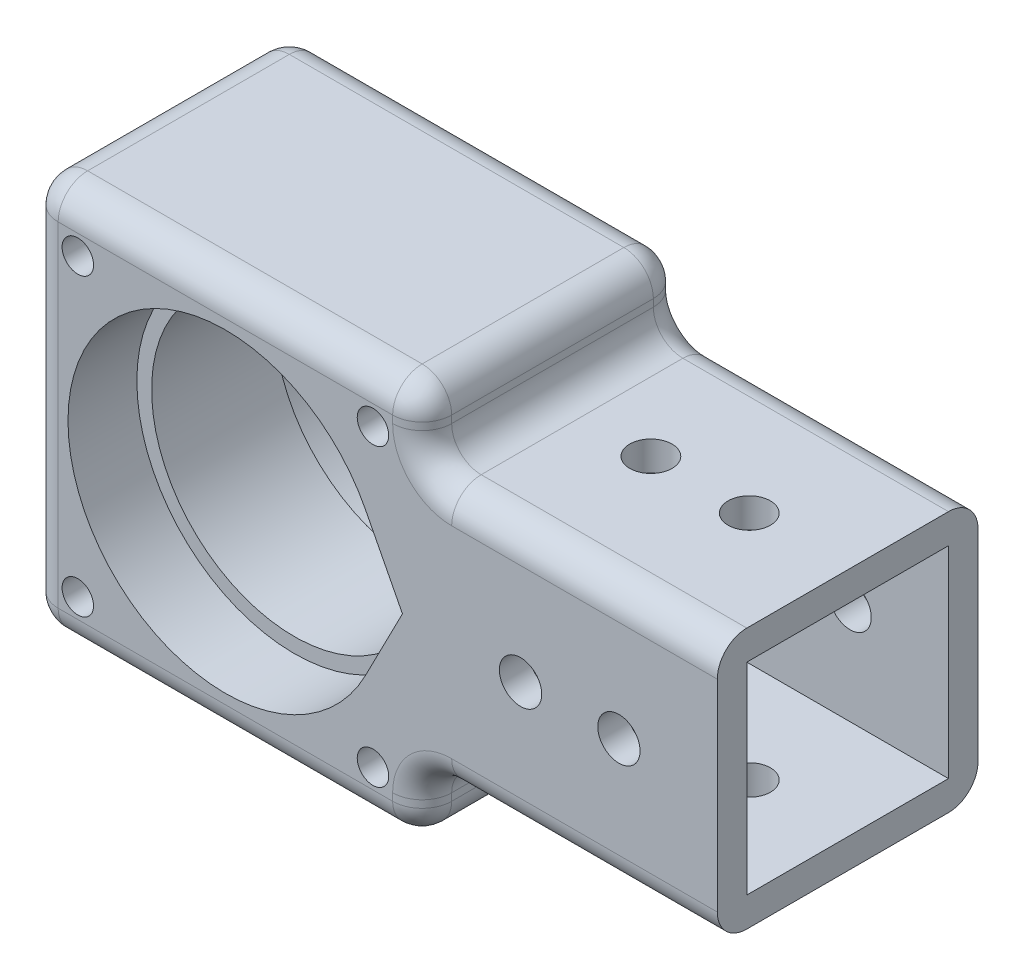
SolidWorks part; units mm, degrees
ref_plane "前视基准面" through (0, 0, 0) normal (0, 0, 1) x (1, 0, 0)
ref_plane "上视基准面" through (0, 0, 0) normal (0, 1, 0) x (1, 0, 0)
ref_plane "右视基准面" through (0, 0, 0) normal (1, 0, 0) x (0, 0, -1)
other "Configuration Table"
sketch "草图1" plane through (0, 0, 0) normal (1, 0, 0) x (0, 0, -1)
  line L1 (-8.75, -8.75) -> (8.75, -8.75)
  line L2 (-8.75, -8.75) -> (-8.75, 8.75)
  line L3 (-8.75, 8.75) -> (8.75, 8.75)
  line L4 (8.75, -8.75) -> (8.75, 8.75)
  line L5 (-8.75, -8.75) -> (8.75, 8.75) construction
  line L6 (-8.75, 8.75) -> (8.75, -8.75) construction
  point P0 (0, 0)
  dimension "D1" = 17.5
  dimension "D2" = 17.5
extrude "凸台-拉伸1" add sketch "草图1" along normal blind 30
sketch "草图2" plane through (0, 0, 0) normal (-1, 0, 0) x (0, 0, 1)
  line L1 (-8.75, -8.75) -> (8.75, -8.75)
  line L2 (-8.75, -8.75) -> (-8.75, 8.75)
  line L3 (-8.75, 8.75) -> (8.75, 8.75)
  line L4 (8.75, -8.75) -> (8.75, 8.75)
  line L5 (-8.75, -8.75) -> (8.75, 8.75) construction
  line L6 (-8.75, 8.75) -> (8.75, -8.75) construction
  line L7 (-10.25, -10.25) -> (10.25, -10.25)
  line L8 (-10.25, -10.25) -> (-10.25, 10.25)
  line L9 (-10.25, 10.25) -> (10.25, 10.25)
  line L10 (10.25, -10.25) -> (10.25, 10.25)
  line L11 (-10.25, -10.25) -> (10.25, 10.25) construction
  line L12 (-10.25, 10.25) -> (10.25, -10.25) construction
  point P0 (0, 0)
  point P7 (0, 0)
  dimension "D1" = 20.5
  dimension "D2" = 20.5
extrude "凸台-拉伸2" add sketch "草图2" against normal blind 2
sketch "草图3" plane through (0, 0, 0) normal (-1, 0, 0) x (0, 0, 1)
  line L5 (-10.25, -10.25) -> (10.25, -10.25)
  line L6 (-10.25, -10.25) -> (-10.25, 10.25)
  line L7 (-10.25, 10.25) -> (10.25, 10.25)
  line L8 (13.25, -13.25) -> (13.25, 13.25)
  line L9 (13.25, 13.25) -> (-13.25, 13.25)
  line L10 (-13.25, 13.25) -> (-13.25, -13.25)
  line L11 (-13.25, -13.25) -> (13.25, -13.25)
  line L12 (13.25, -13.25) -> (13.25, 13.25)
  line L13 (13.25, 13.25) -> (-13.25, 13.25)
  line L14 (-13.25, 13.25) -> (-13.25, -13.25)
  line L15 (-13.25, -13.25) -> (13.25, -13.25)
  line L16 (10.25, -10.25) -> (10.25, 10.25)
  line L17 (-10.25, -10.25) -> (10.25, 10.25) construction
  line L18 (-10.25, 10.25) -> (10.25, -10.25) construction
  point P0 (0, 0)
  dimension "D1" = 3
extrude "凸台-拉伸3" add sketch "草图3" against normal blind 30
sketch "草图4" plane through (0, 13.25, 0) normal (0, 1, 0) x (1, 0, 0)
  line L0 (-1000, 0) -> (49000, 0) construction
  line L1 (0, -13.25) -> (0, 13.25) construction
  circle A0 centre (10, 0) radius 2.15
  circle A1 centre (20, 0) radius 2.15
  dimension "D1" = 4.3
  dimension "D2" = 4.3
  dimension "D4" = 10
  dimension "D5" = 10
sketch "草图5" plane through (0, 0, -13.25) normal (0, 0, -1) x (-1, 0, 0)
  line L1 (-1030, 0) -> (48970, 0) construction
  line L2 (-30, 13.25) -> (-30, -13.25) construction
  line L3 (0, 13.25) -> (0, -13.25) construction
  circle A0 centre (-20, 0) radius 2.15
  circle A1 centre (-10, 0) radius 2.15
  point P7 (-30, 0)
  dimension "D3" = 4.3
  dimension "D4" = 4.3
  dimension "D1" = 10
  dimension "D2" = 10
sketch "草图6" plane through (0, 0, 0) normal (-1, 0, 0) x (0, 0, 1)
  line L0 (-13.25, 2.15) -> (-13.25, -2.15) construction
  line L5 (-23.25, -20) -> (-3.25, -20)
  line L6 (-23.25, -20) -> (-23.25, 20)
  line L7 (-23.25, 20) -> (-3.25, 20)
  line L8 (-3.25, -20) -> (-3.25, 20)
  line L9 (-23.25, -20) -> (-3.25, 20) construction
  line L10 (-23.25, 20) -> (-3.25, -20) construction
  line L11 (-13.25, 20) -> (-13.25, -20)
  point P0 (0, 0)
  point P1 (-13.25, 0)
  line M3 (-13.25, -13.25) -> (13.25, -13.25)
  line M5 (13.25, 13.25) -> (-13.25, 13.25)
  line M6 (-13.25, 13.25) -> (-13.25, -13.25)
  dimension "D1" = 20
  dimension "D2" = 40
extrude "切除-拉伸6" cut sketch "草图4" against normal through all
extrude "凸台-拉伸5" add sketch "草图6" along normal blind 40 contours L8 M3 M5 M6 | L7 L11 L8 M5 | L11 L5 L8 M3
sketch "草图14" plane through (0, 0, -13.25) normal (0, 0, -1) x (-1, 0, 0)
  line L0 (20, -1020) -> (20, 48980) construction
  line L1 (0, 20) -> (40, 20)
  line L2 (0, 20) -> (0, -20)
  line L3 (0, -20) -> (40, -20)
  line L4 (40, 20) -> (40, -20)
  line L5 (-201030, 0) -> (248970, 0) construction
  line L7 (0, 20) -> (5, 20)
  line L8 (0, 20) -> (0, 15)
  line L9 (0, 15) -> (5, 15)
  line L10 (5, 20) -> (5, 15)
  circle A0 centre (20, 0) radius 15
  circle A1 centre (5, 15) radius 1.6
  circle A2 centre (35, 15) radius 1.6
  circle A3 centre (35, -15) radius 1.6
  circle A4 centre (5, -15) radius 1.6
  point P9 (20, -20)
  dimension "D1" = 30
  dimension "D4" = 3.2
  dimension "D2" = 5
  dimension "D3" = 5
  dimension "D5" = 4
extrude "切除-拉伸9" cut sketch "草图14" against normal through all contours A0 L0 | L0 A0 | A4 | A3 | A2 | A1
extrude "切除-拉伸10" cut sketch "草图5" against normal through all
sketch "草图15" plane through (30, 0, 0) normal (1, 0, 0) x (0, 0, -1)
  line L1 (-8.75, -8.75) -> (8.75, -8.75)
  line L2 (-8.75, -8.75) -> (-8.75, 8.75)
  line L3 (-8.75, 8.75) -> (8.75, 8.75)
  line L4 (8.75, -8.75) -> (8.75, 8.75)
  line L5 (-8.75, -8.75) -> (8.75, 8.75) construction
  line L6 (-8.75, 8.75) -> (8.75, -8.75) construction
  point P0 (0, 0)
extrude "切除-拉伸12" cut sketch "草图15" against normal blind 28
sketch "草图16" plane through (0, 0, -3.25) normal (0, 0, 1) x (1, 0, 0)
  line L0 (-20, 0) -> (-3, 0)
  line L1 (-3, 0) -> (-6.7961, 7.1174)
  line L2 (-3, 0) -> (-6.7647, -7.0587)
  line L3 (-6.7647, -7.0587) -> (-6.7961, 7.1174)
  circle A0 centre (-20, 0) radius 15 construction
  circle M19 centre (-20, 0) radius 15
  dimension "D1" = 17
extrude "切除-拉伸13" cut sketch "草图16" against normal blind 28 contours L0 L1 M19 | L2 L0 M19
sketch "草图17" plane through (0, 20, 0) normal (0, 1, 0) x (1, 0, 0)
  line L0 (-20, 13.25) -> (-20, 3.25)
  line L1 (-40, 13.25) -> (0, 13.25) construction
  line L2 (-40, 3.25) -> (0, 3.25) construction
  circle A0 centre (-20, 8.25) radius 1.5
  dimension "D1" = 3
extrude "切除-拉伸14" cut sketch "草图17" against normal through all contours L0 A0 | L0 A0
sketch "草图18" plane through (0, 0, -3.25) normal (0, 0, 1) x (1, 0, 0)
  circle A0 centre (-20, 0) radius 16
  dimension "D1" = 32
extrude "切除-拉伸15" cut sketch "草图18" against normal blind 10
sketch "草图19" plane through (0, 0, -3.25) normal (0, 0, 1) x (1, 0, 0)
  line L0 (-3, 0) -> (-20, 0)
  line L1 (-3, 0) -> (-2, 0)
  line L2 (-2, 0) -> (-5.7778, 7.33)
  line L3 (-2, 0) -> (-5.7778, -7.33)
  line L4 (-5.7778, -7.33) -> (-5.7778, 7.33)
  arc A0 (-4.1446, 2.146) -> (-4.1446, -2.1461) centre (-20, 0) ccw construction
  line M5 (-3, 0) -> (-4.1446, -2.1461)
  arc M6 (-4.1446, -2.1461) -> (-4.1446, 2.146) centre (-20, 0) cw
  line M7 (-4.1446, 2.146) -> (-3, 0)
  dimension "D1" = 18
extrude "切除-拉伸16" cut sketch "草图19" against normal blind 10 contours L1 L2 M6 M7 | L3 L1 M5 M6
sketch "草图20" plane through (0, 0, -3.25) normal (0, 0, 1) x (1, 0, 0)
  line L1 (0, 20) -> (-40.3354, 20)
  line L2 (0, 20) -> (0, -20)
  line L3 (0, -20) -> (-40.3354, -20)
  line L4 (-40.3354, 20) -> (-40.3354, -20)
extrude "切除-拉伸17" cut sketch "草图20" against normal blind 3
sketch "草图21" plane through (0, -20, 0) normal (0, -1, 0) x (1, 0, 0)
  circle A0 centre (-20, -8.25) radius 1.5
extrude "凸台-拉伸6" add sketch "草图21" against normal blind 40
sketch "草图22" plane through (0, 0, -6.25) normal (0, 0, 1) x (1, 0, 0)
  circle A0 centre (-20, 0) radius 16
extrude "切除-拉伸18" cut sketch "草图22" against normal blind 40
sketch "草图23" plane through (0, -20, 0) normal (0, -1, 0) x (1, 0, 0)
  line L0 (-20, -6.25) -> (-20, -9.75)
  line L1 (-40, -6.25) -> (0, -6.25) construction
  circle A0 centre (-20, -9.75) radius 1.85
  dimension "D2" = 3.7
  dimension "D1" = 3.5
sketch "草图24" plane through (0, 0, -6.25) normal (0, 0, 1) x (1, 0, 0)
  line L1 (-40, 20) -> (0, 20)
  line L2 (-40, 20) -> (-40, -20)
  line L3 (-40, -20) -> (0, -20)
  line L4 (0, 20) -> (0, -20)
  circle A0 centre (-35, 15) radius 1.6
  circle A1 centre (-35, -15) radius 1.6
  circle A2 centre (-5, -15) radius 1.6
  circle A3 centre (-5, 15) radius 1.6
  circle A4 centre (-20, 0) radius 14.5
  dimension "D1" = 29
extrude "凸台-拉伸7" add sketch "草图24" along normal blind 12.5
sketch "草图25" plane through (0, 0, 6.25) normal (0, 0, 1) x (1, 0, 0)
  line L0 (-20, 0) -> (-2, 0)
  line L1 (-2, 0) -> (-5.7778, 7.33)
  line L2 (-5.7778, 7.33) -> (-5.7778, -7.33)
  line L3 (-5.7778, -7.33) -> (-2, 0)
  circle A0 centre (-20, 0) radius 16
  circle A1 centre (-35, 15) radius 1.6
  circle A2 centre (-5, 15) radius 1.6
  circle A3 centre (-5, -15) radius 1.6
  circle A4 centre (-35, -15) radius 1.6
  circle M1 centre (-5, 15) radius 1.6
  circle M2 centre (-35, -15) radius 1.6
  line M3 (-40, 20) -> (-40, -20)
  line M4 (-40, -20) -> (0, -20)
  line M5 (0, -20) -> (0, -13.25)
  line M6 (0, -13.25) -> (0, 13.25)
  line M7 (0, 13.25) -> (0, 20)
  line M8 (0, 20) -> (-40, 20)
  circle M9 centre (-35, 15) radius 1.6
  circle M10 centre (-5, -15) radius 1.6
  dimension "D1" = 32
extrude "凸台-拉伸8" add sketch "草图25" along normal blind 7 contours A0 L1 L3 M8 M3 M4 M5 M6 M7 M2 M9 M10 M1
fillet "圆角1" radius 3 1 edges at (0, 20, 0)
fillet "圆角2" radius 3 1 edges at (0, 13.25, 0)
fillet "圆角3" radius 3 1 edges at (-40, 20, 0)
fillet "圆角4" radius 3 1 edges at (-40, -20, 0)
fillet "圆角5" radius 3 1 edges at (0, -20, 0)
fillet "圆角6" radius 3 1 edges at (0, -13.25, 0)
fillet "圆角7" radius 3 13 edges at (0, 16.625, -13.25) (-0.8787, 19.1213, -13.25) (0.8787, 14.1287, -13.25) (-40, 0, -13.25) (-20, 20, -13.25) (16.5, -13.25, -13.25) (-39.1213, 19.1213, -13.25) (16.5, 13.25, -13.25) (-20, -20, -13.25) (-39.1213, -19.1213, -13.25) (-0.8787, -19.1213, -13.25) (0, -16.625, -13.25) (0.8787, -14.1287, -13.25)
fillet "圆角8" radius 3 13 edges at (-20, 20, 13.25) (-0.8787, 19.1213, 13.25) (0, 16.625, 13.25) (0.8787, 14.1287, 13.25) (16.5, -13.25, 13.25) (-40, 0, 13.25) (-39.1213, 19.1213, 13.25) (16.5, 13.25, 13.25) (-20, -20, 13.25) (-39.1213, -19.1213, 13.25) (0, -16.625, 13.25) (-0.8787, -19.1213, 13.25) (0.8787, -14.1287, 13.25)
